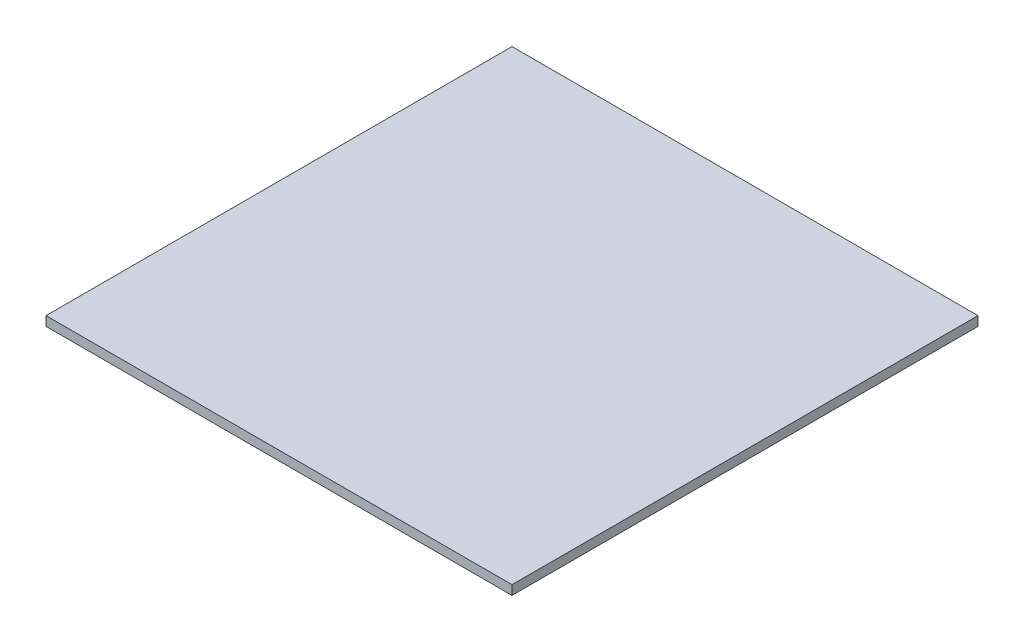
SolidWorks part; units mm, degrees
ref_plane "Alzado" through (0, 0, 0) normal (0, 0, 1) x (1, 0, 0)
ref_plane "Planta" through (0, 0, 0) normal (0, 1, 0) x (1, 0, 0)
ref_plane "Vista lateral" through (0, 0, 0) normal (1, 0, 0) x (0, 0, -1)
sketch "Croquis1" plane through (0, 0, 0) normal (0, 1, 0) x (1, 0, 0)
  line L1 (-250, 0) -> (250, 0)
  line L2 (-250, 0) -> (-250, -500)
  line L3 (-250, -500) -> (250, -500)
  line L4 (250, 0) -> (250, -500)
  dimension "D1" = 500
  dimension "D2" = 500
extrude "Saliente-Extruir1" add sketch "Croquis1" along normal blind 10
